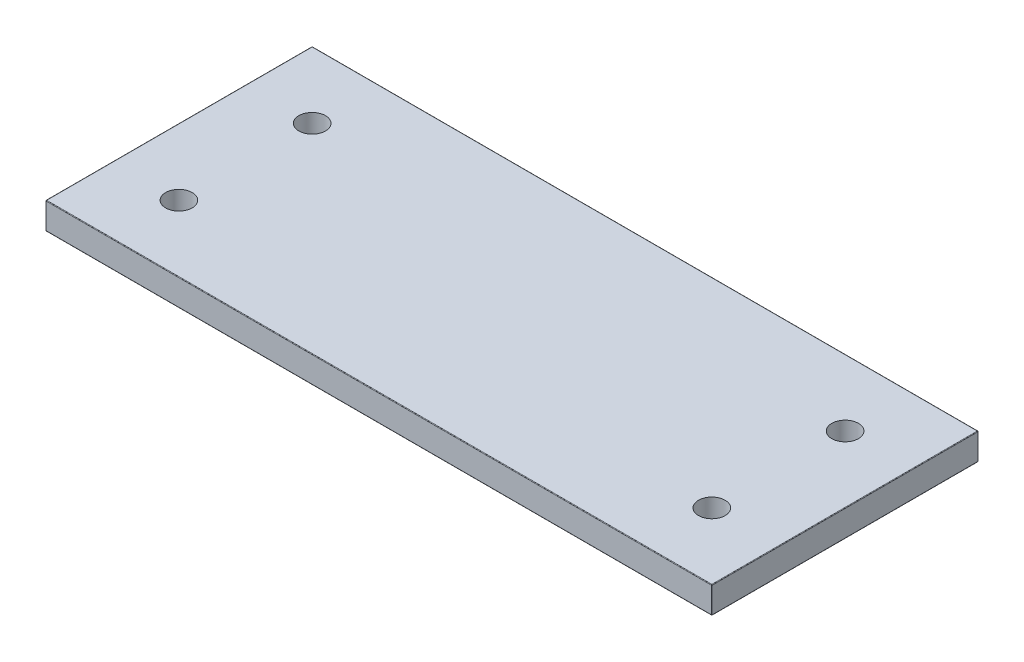
SolidWorks part; units mm, degrees
ref_plane "Front Plane" through (0, 0, 0) normal (0, 0, 1) x (1, 0, 0)
ref_plane "Top Plane" through (0, 0, 0) normal (0, 1, 0) x (1, 0, 0)
ref_plane "Right Plane" through (0, 0, 0) normal (1, 0, 0) x (0, 0, -1)
sketch "Sketch1" plane through (0, 0, 0) normal (0, 1, 0) x (1, 0, 0)
  line L0 (0, 0) -> (174.6374, 0) construction
  line L1 (-125, 50) -> (125, 50)
  line L2 (-125, 50) -> (-125, -50)
  line L3 (-125, -50) -> (125, -50)
  line L4 (125, 50) -> (125, -50)
  line L5 (-125, 50) -> (125, -50) construction
  line L6 (-125, -50) -> (125, 50) construction
  line L7 (0, 0) -> (0, 65.4756) construction
  circle A0 centre (100, 25) radius 5
  circle A1 centre (100, -25) radius 5
  circle A2 centre (-100, -25) radius 5
  circle A3 centre (-100, 25) radius 5
  point P0 (0, 0)
  dimension "D3" = 10
  dimension "D1" = 250
  dimension "D2" = 100
  dimension "D4" = 25
  dimension "D5" = 100
extrude "Boss-Extrude1" add sketch "Sketch1" along normal blind 10
fillet "Fillet1" radius 0.2 12 edges at (-125, 5, 50) (-125, 5, -50) (-125, 0, 0) (-125, 10, 0) (125, 5, -50) (0, 0, -50) (0, 10, -50) (125, 0, 0) (125, 10, 0) (125, 5, 50) (0, 0, 50) (0, 10, 50)
